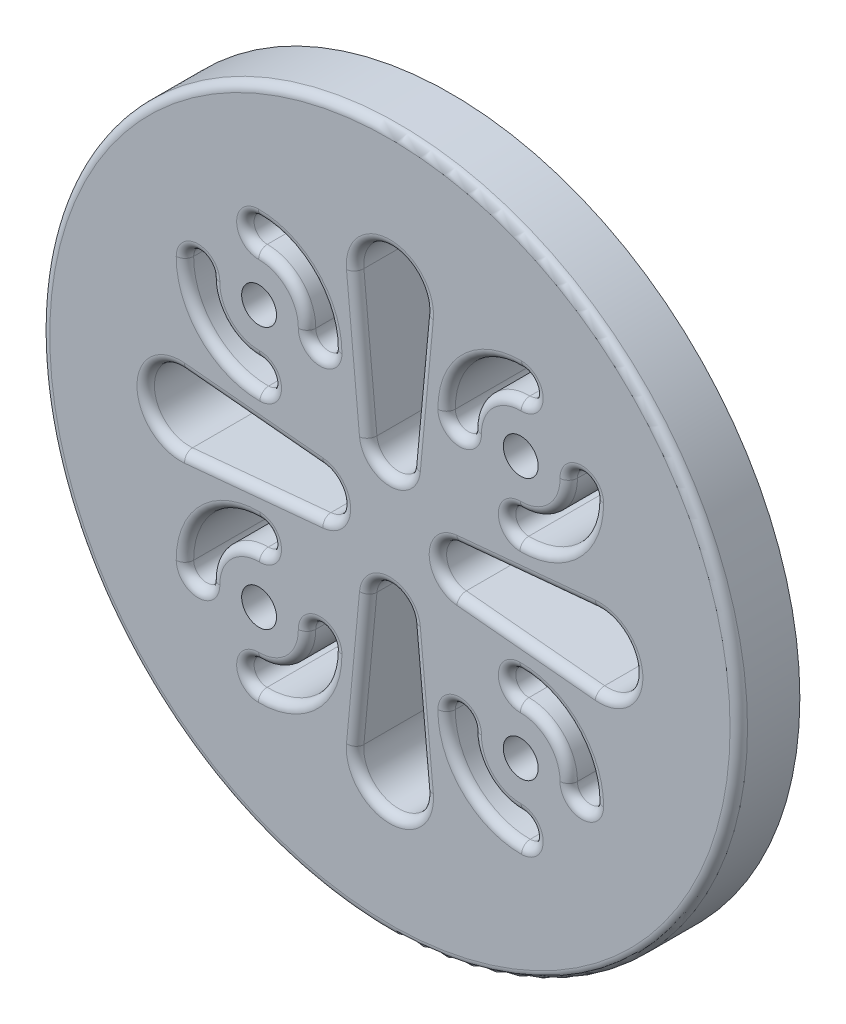
SolidWorks part; units mm, degrees
material "Cast Alloy Steel"
ref_plane "Front Plane" through (0, 0, 0) normal (0, 0, 1) x (1, 0, 0)
ref_plane "Top Plane" through (0, 0, 0) normal (0, 1, 0) x (1, 0, 0)
ref_plane "Right Plane" through (0, 0, 0) normal (1, 0, 0) x (0, 0, -1)
sketch "Sketch2" plane through (0, 0, 0) normal (1, 0, 0) x (0, 0, -1)
  line L0 (0, 0) -> (0, 20)
  line L1 (0, 20) -> (2, 20)
  line L3 (2, 17) -> (5, 17)
  line L4 (5, 17) -> (5, 0)
  line L5 (0, 0) -> (5, 0)
  line L6 (2, 20) -> (3.5, 20)
  line L7 (3.5, 20) -> (3.5, 18.5)
  line L8 (3.5, 18.5) -> (2, 18.5)
  line L9 (2, 18.5) -> (2, 17)
  dimension "D1" = 2
  dimension "D2" = 3
  dimension "D3" = 3
  dimension "D4" = 20
  dimension "D5" = 17
  dimension "D6" = 1.5
revolve "Revolve1" add sketch "Sketch2" angle 360 about L5
sketch "Sketch3" plane through (0, 0, -5) normal (0, 0, -1) x (-1, 0, 0)
  line L1 (7.5, -7.5) -> (-7.5, -7.5) construction
  line L2 (7.5, -7.5) -> (7.5, 7.5) construction
  line L3 (7.5, 7.5) -> (-7.5, 7.5) construction
  line L4 (-7.5, -7.5) -> (-7.5, 7.5) construction
  line L5 (7.5, -7.5) -> (-7.5, 7.5) construction
  line L6 (7.5, 7.5) -> (-7.5, -7.5) construction
  circle A0 centre (-7.5, 7.5) radius 1
  circle A1 centre (7.5, 7.5) radius 1
  circle A2 centre (7.5, -7.5) radius 1
  circle A3 centre (-7.5, -7.5) radius 1
  point P0 (0, 0)
  dimension "D2" = 2
  dimension "D1" = 15
extrude "Cut-Extrude1" cut sketch "Sketch3" against normal blind 20
sketch "Sketch4" plane through (0, 0, 0) normal (0, 0, 1) x (1, 0, 0)
  line L0 (0, 0) -> (0, 12) construction
  line L1 (-1.9912, 11.8125) -> (-1.2445, 3.8828)
  line L2 (1.2445, 3.8828) -> (1.9912, 11.8125)
  line L3 (3.8828, -1.2445) -> (11.8125, -1.9912)
  line L4 (11.8125, 1.9912) -> (3.8828, 1.2445)
  line L5 (-1.2445, -3.8828) -> (-1.9912, -11.8125)
  line L6 (1.9912, -11.8125) -> (1.2445, -3.8828)
  line L7 (-3.8828, 1.2445) -> (-11.8125, 1.9912)
  line L8 (-11.8125, -1.9912) -> (-3.8828, -1.2445)
  arc A0 (-1.9912, 11.8125) -> (1.9912, 11.8125) centre (0, 12) cw
  arc A1 (-1.2445, 3.8828) -> (1.2445, 3.8828) centre (0, 4) ccw
  arc A2 (11.8125, 1.9912) -> (11.8125, -1.9912) centre (12, 0) cw
  arc A3 (3.8828, 1.2445) -> (3.8828, -1.2445) centre (4, 0) ccw
  arc A4 (1.9912, -11.8125) -> (-1.9912, -11.8125) centre (0, -12) cw
  arc A5 (1.2445, -3.8828) -> (-1.2445, -3.8828) centre (0, -4) ccw
  arc A6 (-11.8125, -1.9912) -> (-11.8125, 1.9912) centre (-12, 0) cw
  arc A7 (-3.8828, -1.2445) -> (-3.8828, 1.2445) centre (-4, 0) ccw
  point P29 (0, 0)
  point P30 (0, 0)
  dimension "D3" = 2
  dimension "D4" = 1.25
  dimension "D1" = 12
  dimension "D2" = 4
  dimension "D5" = 4
extrude "Cut-Extrude2" cut sketch "Sketch4" against normal blind 20
fillet "Fillet3" radius 0.5 1 edges at (20, 0, 0)
fillet "Fillet4" radius 0.5 16 edges at (14, 0, 0) (7.8477, -1.6178, 0) (2.75, 0, 0) (0, -14, 0) (-1.6178, -7.8477, 0) (0, -2.75, 0) (-2.75, 0, 0) (-7.8477, -1.6178, 0) (-14, 0, 0) (0, 2.75, 0) (-1.6178, 7.8477, 0) (0, 14, 0) (7.8477, 1.6178, 0) (1.6178, -7.8477, 0) (-7.8477, 1.6178, 0) (1.6178, 7.8477, 0)
sketch "Sketch5" plane through (0, 0, 0) normal (0, 0, 1) x (1, 0, 0)
  line L0 (-7.5, 8.5) -> (-7.5, 6.5) construction
  line L1 (0, 0) -> (-7.5, 7.5) construction
  line L2 (-7.5, 7.5) -> (-5.0251, 9.9749) construction
  circle A0 centre (-7.5, 7.5) radius 1 construction
  arc A1 (-7.5357, 10.9998) -> (-4.0002, 7.4643) centre (-7.5, 7.5) cw construction
  arc A2 (-7.5281, 10.2499) -> (-4.7501, 7.4719) centre (-7.5, 7.5) cw
  arc A3 (-7.5434, 11.7498) -> (-3.2502, 7.4566) centre (-7.5, 7.5) cw
  arc A4 (-7.5281, 10.2499) -> (-7.5434, 11.7498) centre (-7.5357, 10.9998) cw
  arc A5 (-4.7501, 7.4719) -> (-3.2502, 7.4566) centre (-4.0002, 7.4643) ccw
  arc A6 (-10.2499, 7.5281) -> (-7.4719, 4.7501) centre (-7.5, 7.5) ccw
  arc A7 (-10.2499, 7.5281) -> (-11.7498, 7.5434) centre (-10.9998, 7.5357) ccw
  arc A8 (-11.7498, 7.5434) -> (-7.4566, 3.2502) centre (-7.5, 7.5) ccw
  arc A9 (-7.4719, 4.7501) -> (-7.4566, 3.2502) centre (-7.4643, 4.0002) cw
  arc A10 (7.5281, 10.2499) -> (4.7501, 7.4719) centre (7.5, 7.5) ccw
  arc A11 (4.7501, 7.4719) -> (3.2502, 7.4566) centre (4.0002, 7.4643) cw
  arc A12 (7.5434, 11.7498) -> (3.2502, 7.4566) centre (7.5, 7.5) ccw
  arc A13 (7.5281, 10.2499) -> (7.5434, 11.7498) centre (7.5357, 10.9998) ccw
  arc A14 (7.4719, 4.7501) -> (7.4566, 3.2502) centre (7.4643, 4.0002) ccw
  arc A15 (11.7498, 7.5434) -> (7.4566, 3.2502) centre (7.5, 7.5) cw
  arc A16 (10.2499, 7.5281) -> (11.7498, 7.5434) centre (10.9998, 7.5357) cw
  arc A17 (10.2499, 7.5281) -> (7.4719, 4.7501) centre (7.5, 7.5) cw
  arc A18 (10.2499, -7.5281) -> (7.4719, -4.7501) centre (7.5, -7.5) ccw
  arc A19 (7.4719, -4.7501) -> (7.4566, -3.2502) centre (7.4643, -4.0002) cw
  arc A20 (11.7498, -7.5434) -> (7.4566, -3.2502) centre (7.5, -7.5) ccw
  arc A21 (10.2499, -7.5281) -> (11.7498, -7.5434) centre (10.9998, -7.5357) ccw
  arc A22 (4.7501, -7.4719) -> (3.2502, -7.4566) centre (4.0002, -7.4643) ccw
  arc A23 (7.5434, -11.7498) -> (3.2502, -7.4566) centre (7.5, -7.5) cw
  arc A24 (7.5281, -10.2499) -> (7.5434, -11.7498) centre (7.5357, -10.9998) cw
  arc A25 (7.5281, -10.2499) -> (4.7501, -7.4719) centre (7.5, -7.5) cw
  arc A26 (-7.5281, -10.2499) -> (-4.7501, -7.4719) centre (-7.5, -7.5) ccw
  arc A27 (-4.7501, -7.4719) -> (-3.2502, -7.4566) centre (-4.0002, -7.4643) cw
  arc A28 (-7.5434, -11.7498) -> (-3.2502, -7.4566) centre (-7.5, -7.5) ccw
  arc A29 (-7.5281, -10.2499) -> (-7.5434, -11.7498) centre (-7.5357, -10.9998) ccw
  arc A30 (-7.4719, -4.7501) -> (-7.4566, -3.2502) centre (-7.4643, -4.0002) ccw
  arc A31 (-11.7498, -7.5434) -> (-7.4566, -3.2502) centre (-7.5, -7.5) cw
  arc A32 (-10.2499, -7.5281) -> (-11.7498, -7.5434) centre (-10.9998, -7.5357) cw
  arc A33 (-10.2499, -7.5281) -> (-7.4719, -4.7501) centre (-7.5, -7.5) cw
  point P70 (0, 0)
  dimension "D1" = 3.5
  dimension "D2" = 5
  dimension "D3" = 0.75
  dimension "D4" = 0.75
  dimension "D5" = 4
extrude "Cut-Extrude3" cut sketch "Sketch5" against normal blind 10
fillet "Fillet5" radius 0.5 32 edges at (10.9922, -8.2857, 0) (9.4445, -5.5555, 0) (6.7143, -4.0078, 0) (8.2857, -10.9922, 0) (4.4948, -10.5052, 0) (4.0078, -6.7143, 0) (-4.0078, -6.7143, 0) (-4.4948, -10.5052, 0) (-8.2857, -10.9922, 0) (-6.7143, -4.0078, 0) (-9.4445, -5.5555, 0) (-10.9922, -8.2857, 0) (-6.7143, 4.0078, 0) (-10.5052, 4.4948, 0) (-10.9922, 8.2857, 0) (10.9922, 8.2857, 0) (10.5052, 4.4948, 0) (6.7143, 4.0078, 0) (8.2857, 10.9922, 0) (5.5555, 9.4445, 0) (4.0078, 6.7143, 0) (-4.0078, 6.7143, 0) (-5.5555, 9.4445, 0) (-8.2857, 10.9922, 0) (10.5052, -4.4948, 0) (5.5555, -9.4445, 0) (-5.5555, -9.4445, 0) (-10.5052, -4.4948, 0) (-9.4445, 5.5555, 0) (9.4445, 5.5555, 0) (4.4948, 10.5052, 0) (-4.4948, 10.5052, 0)
